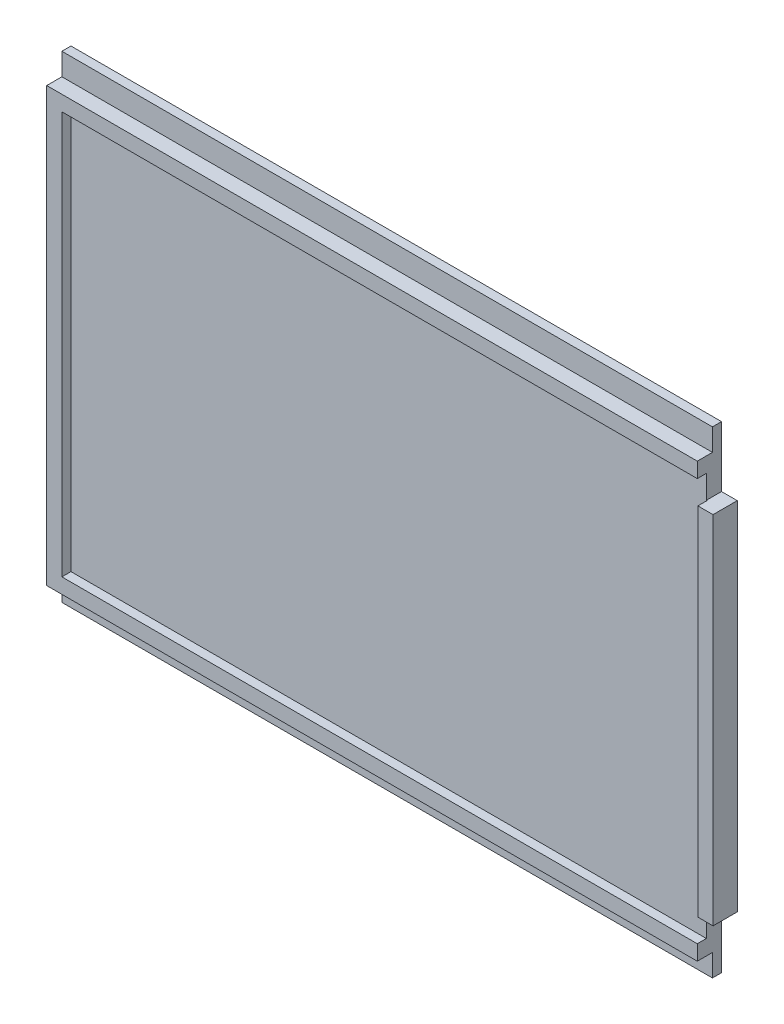
SolidWorks part; units mm, degrees
ref_plane "Alzado" through (0, 0, 0) normal (0, 0, 1) x (1, 0, 0)
ref_plane "Planta" through (0, 0, 0) normal (0, 1, 0) x (1, 0, 0)
ref_plane "Vista lateral" through (0, 0, 0) normal (1, 0, 0) x (0, 0, -1)
sketch "Croquis1" plane through (0, 0, 0) normal (0, 0, 1) x (1, 0, 0)
  line L1 (-110, 71.5) -> (110, 71.5)
  line L2 (-110, 71.5) -> (-110, -71.5)
  line L3 (-110, -71.5) -> (110, -71.5)
  line L4 (110, 71.5) -> (110, -71.5)
  line L5 (-110, 71.5) -> (110, -71.5) construction
  line L6 (-110, -71.5) -> (110, 71.5) construction
  point P0 (0, 0)
  dimension "D1" = 220
  dimension "D2" = 143
extrude "Saliente-Extruir1" add sketch "Croquis1" along normal blind 5
sketch "Croquis2" plane through (0, 0, 5) normal (0, 0, 1) x (1, 0, 0)
  line L0 (110, 71.5) -> (-110, 71.5) construction
  line L1 (105, -66.5) -> (-105, -66.5)
  line L2 (105, -66.5) -> (105, 66.5)
  line L3 (105, 66.5) -> (-105, 66.5)
  line L4 (-105, -66.5) -> (-105, 66.5)
  line L5 (105, -66.5) -> (-105, 66.5) construction
  line L6 (105, 66.5) -> (-105, -66.5) construction
  line L7 (-110, 71.5) -> (-110, -71.5) construction
  point P0 (0, 0)
  dimension "D1" = 5
  dimension "D2" = 5
extrude "Cortar-Extruir1" cut sketch "Croquis2" against normal blind 3
sketch "Croquis3" plane through (0, 0, 0) normal (0, 0, -1) x (-1, 0, 0)
  line L1 (-110, 78.8) -> (110, 78.8)
  line L2 (-110, 78.8) -> (-110, -78.8)
  line L3 (-110, -78.8) -> (110, -78.8)
  line L4 (110, 78.8) -> (110, -78.8)
  line L5 (-110, 78.8) -> (110, -78.8) construction
  line L6 (-110, -78.8) -> (110, 78.8) construction
  line L8 (110, -71.5) -> (-110, -71.5) construction
  line L9 (-110, -71.5) -> (-110, 71.5) construction
  point P0 (0, 0)
  dimension "D1" = 157.6
  dimension "D2" = 7.3
  dimension "D3" = 220
extrude "Saliente-Extruir2" add sketch "Croquis3" along normal blind 3
sketch "Croquis4" plane through (0, 0, -3) normal (0, 0, -1) x (-1, 0, 0)
  line L0 (-104.8, 78.8) -> (-104.8, 58.8)
  line L1 (110, 78.8) -> (-110, 78.8) construction
  line L2 (-110, -78.8) -> (110, -78.8) construction
  line L3 (-110, 78.8) -> (-110, -78.8) construction
  line L4 (-104.8, 58.8) -> (-110, 58.8)
  line L6 (-110, -58.8) -> (-104.8, -58.8)
  line L7 (-110, 58.8) -> (-110, 78.8)
  line L8 (-110, 78.8) -> (-104.8, 78.8)
  line L9 (-110, -58.8) -> (-110, -78.8)
  line L10 (-110, -78.8) -> (-104.8, -78.8)
  line L11 (-104.8, -58.8) -> (-104.8, -78.8)
  dimension "D1" = 5.2
  dimension "D2" = 20
  dimension "D3" = 20
extrude "Cortar-Extruir2" cut sketch "Croquis4" against normal through all
